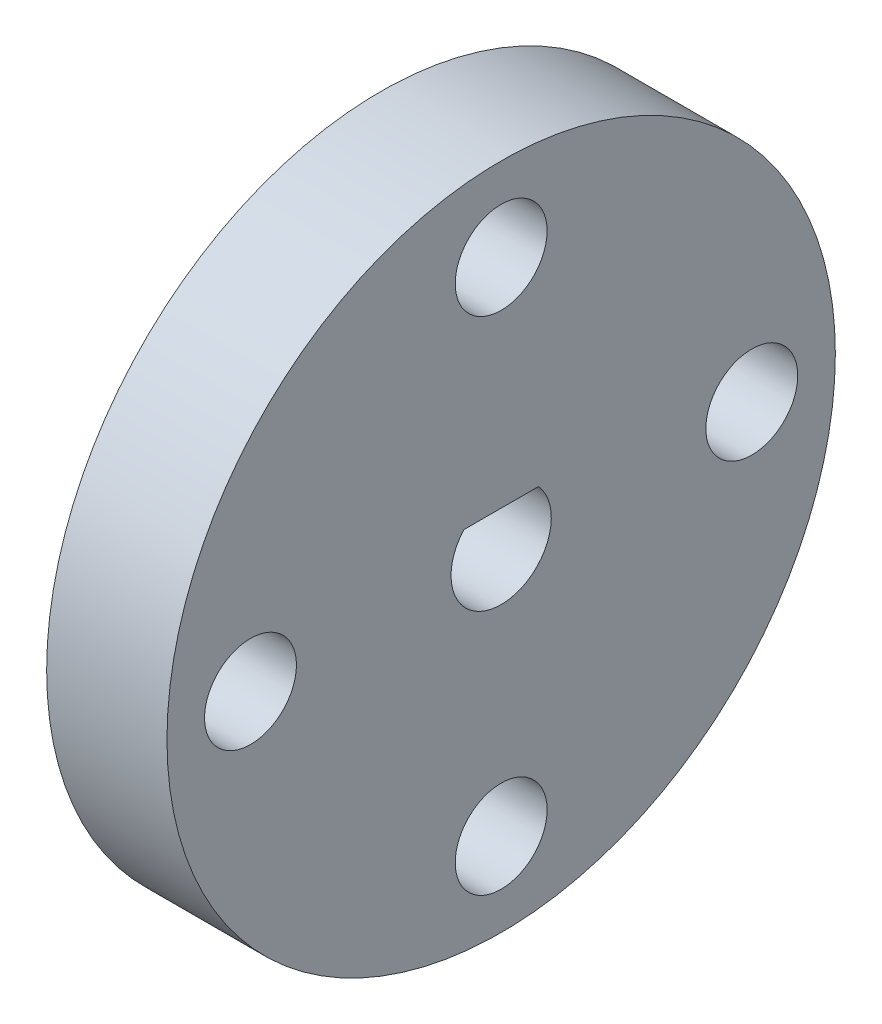
SolidWorks part; units mm, degrees
material "Barra Redonda SAE 1020 - 2\""
ref_plane "Plano frontal" through (0, 0, 0) normal (0, 0, 1) x (1, 0, 0)
ref_plane "Plano superior" through (0, 0, 0) normal (0, 1, 0) x (1, 0, 0)
ref_plane "Plano direito" through (0, 0, 0) normal (1, 0, 0) x (0, 0, -1)
sketch "Esboço1" plane through (0, 0, 0) normal (0, 0, 1) x (1, 0, 0)
  line L0 (-35, 0) -> (35, 0) construction
  line L1 (0, 0) -> (0, 20)
  line L2 (0, 0) -> (7.2, 0)
  line L3 (7.2, 0) -> (7.2, 20)
  line L4 (0, 20) -> (7.2, 20)
  dimension "D1" = 40
  dimension "D3" = 7.2
revolve "Revolução1" add sketch "Esboço1" angle 360 about L0
sketch "Esboço3" plane through (7.2, 0, 0) normal (1, 0, 0) x (0, 0, -1)
  line L0 (-2.2361, 2) -> (2.2361, 2)
  arc A0 (-2.2361, 2) -> (2.2361, 2) centre (0, 0) ccw
  dimension "D1" = 6
  dimension "D2" = 2
extrude "Corte-extrusão2" cut sketch "Esboço3" against normal through all
hole_wizard "Furo com folga de M51" positions "Esboço6" profile "Esboço5" hole size "M5" standard "ISO" end condition through all
sketch "Esboço6" plane through (7.2, 0, 0) normal (1, 0, 0) x (0, 0, -1)
  point P0 (0, 15)
  point P2 (15, 0)
  point P4 (0, -15)
  point P6 (-15, 0)
  dimension "D1" = 15
  dimension "D2" = 15
  dimension "D3" = 15
  dimension "D4" = 15
sketch "Esboço5" plane through (7.2, 15, 0) normal (0, 1, 0) x (0, 0, -1)
  line L0 (0, 0) -> (0, 7.2)
  line L1 (0, 7.2) -> (2.75, 7.2)
  line L2 (2.75, 7.2) -> (2.75, 0)
  line L5 (2.75, 0) -> (0, 0)
  line L11 (0, -6.35) -> (0, 107.95) construction
  dimension "Thru Hole Dia." = 5.5
  dimension "Thru Hole Depth" = 7.2
